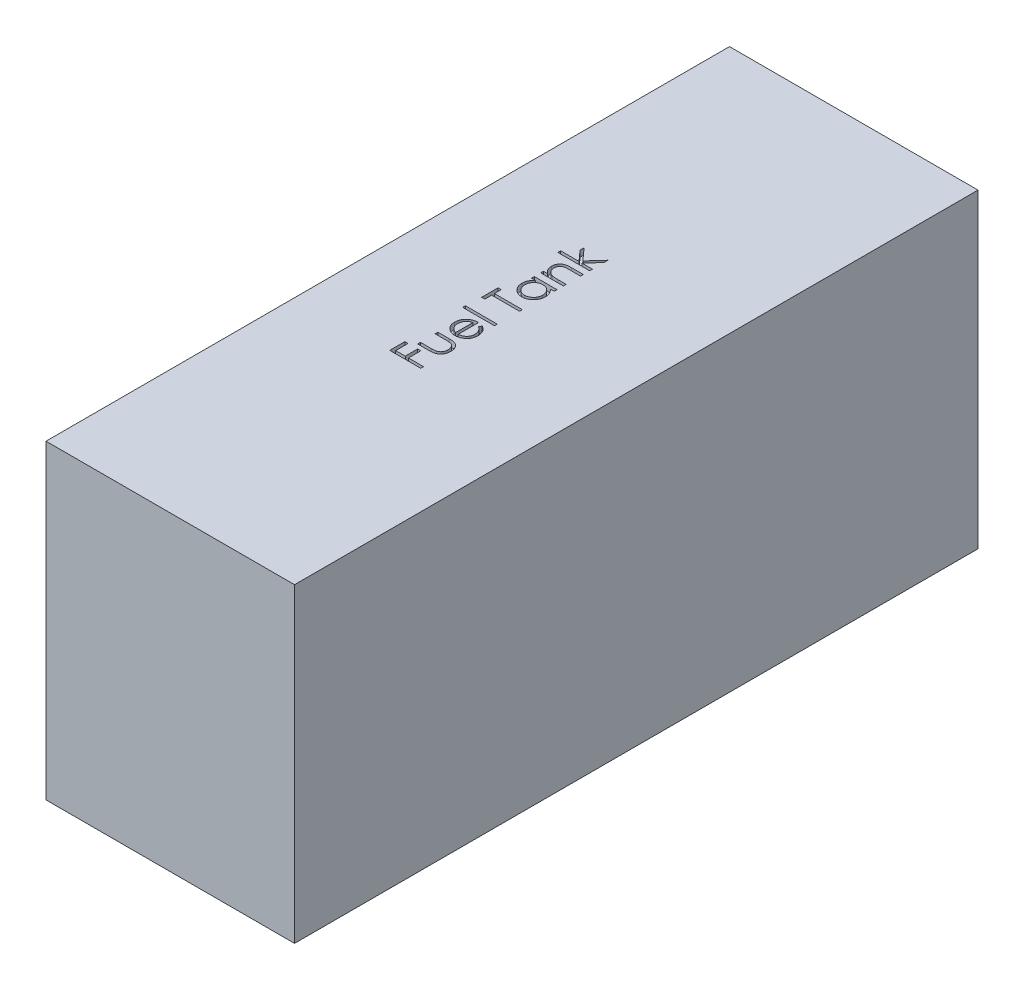
SolidWorks part; units mm, degrees
ref_plane "Front Plane" through (0, 0, 0) normal (0, 0, 1) x (1, 0, 0)
ref_plane "Top Plane" through (0, 0, 0) normal (0, 1, 0) x (1, 0, 0)
ref_plane "Right Plane" through (0, 0, 0) normal (1, 0, 0) x (0, 0, -1)
sketch "Sketch1" plane through (0, 0, 0) normal (0, 1, 0) x (1, 0, 0)
  line L1 (-40, 110) -> (40, 110)
  line L2 (-40, 110) -> (-40, -110)
  line L3 (-40, -110) -> (40, -110)
  line L4 (40, 110) -> (40, -110)
  line L5 (-40, 110) -> (40, -110) construction
  line L6 (-40, -110) -> (40, 110) construction
  point P0 (0, 0)
  dimension "D1" = 80
  dimension "D2" = 220
extrude "Boss-Extrude1" add sketch "Sketch1" along normal blind 100
sketch "Sketch2" plane through (0, 100, 0) normal (0, 1, 0) x (1, 0, 0)
  line L0 (0, -110) -> (0, 110) construction
  line L1 (-40, -110) -> (40, -110) construction
  line L2 (40, 110) -> (-40, 110) construction
  text T0 "Fuel Tank" font "Century Gothic" height 10
extrude "Cut-Extrude1" cut sketch "Sketch2" against normal blind 2
